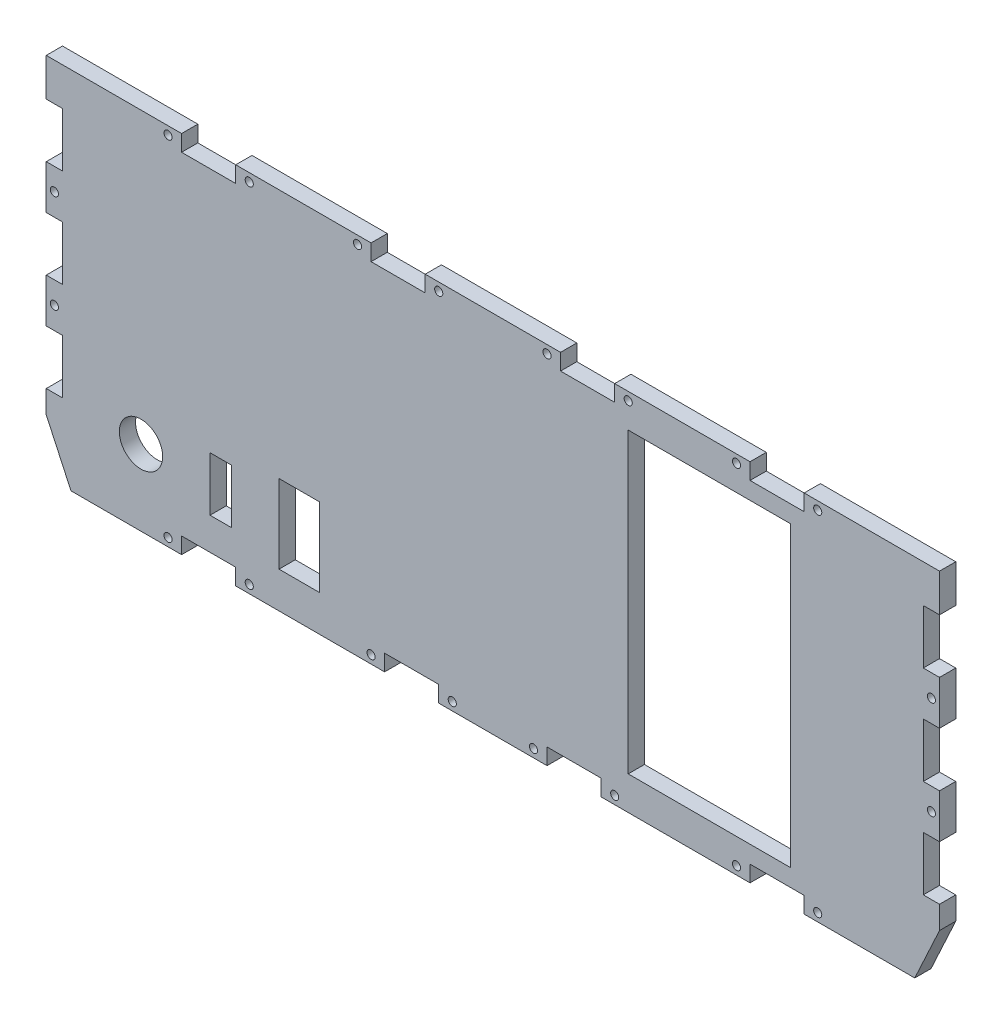
SolidWorks part; units mm, degrees
ref_plane "Plan de face" through (0, 0, 0) normal (0, 0, 1) x (1, 0, 0)
ref_plane "Plan de dessus" through (0, 0, 0) normal (0, 1, 0) x (1, 0, 0)
ref_plane "Plan de droite" through (0, 0, 0) normal (1, 0, 0) x (0, 0, -1)
sketch "Esquisse1" plane through (0, 0, 0) normal (0, 0, 1) x (1, 0, 0)
  line L0 (0, 124.9429) -> (0, -204.46) construction
  line L1 (-165, 96.73) -> (165, 96.73)
  line L2 (165, 96.73) -> (165, -18.27)
  line L3 (165, -18.27) -> (123, -109.0224)
  line L4 (123, -109.0224) -> (-123, -109.0224)
  line L5 (-211.9802, 0) -> (248.5953, 0) construction
  line L6 (-123, -109.0224) -> (-165, -18.27)
  line L7 (-165, -18.27) -> (-165, 96.73)
  dimension "D2" = 165
  dimension "D3" = 330
  dimension "D4" = 100
  dimension "D5" = 115
  dimension "D6" = 100
  dimension "D7" = 246
  dimension "D8" = 205.7524
  dimension "D9" = 96.73
  dimension "D10" = 115
extrude "Boss.-Extru.1" add sketch "Esquisse1" along normal blind 6
sketch "Esquisse3" plane through (0, 0, 0) normal (0, 0, -1) x (-1, 0, 0)
  line L0 (165, 96.73) -> (165, -18.27) construction
  line L1 (159, 46.44) -> (159, 26.44)
  line L2 (165, 46.44) -> (159, 46.44)
  line L3 (159, 82.73) -> (159, 62.73)
  line L4 (165, 62.73) -> (159, 62.73)
  line L5 (123, -109.0224) -> (-123, -109.0224) construction
  line L6 (165, 82.73) -> (165, 62.73)
  line L7 (165, 82.73) -> (159, 82.73)
  line L8 (159, 10.15) -> (159, -9.85)
  line L9 (165, -9.85) -> (159, -9.85)
  line L10 (-20, -38.02) -> (-20, -32.02)
  line L11 (115, -38.02) -> (95, -38.02)
  line L12 (115, -38.02) -> (115, -32.02)
  line L13 (115, -32.02) -> (95, -32.02)
  line L15 (0, -209.4812) -> (0, 177.1799) construction
  line L16 (-110, 84.355) -> (-50, 84.355)
  line L17 (-165, 82.73) -> (-159, 82.73)
  line L18 (95, -38.02) -> (95, -32.02)
  line L19 (40, -38.02) -> (20, -38.02)
  line L20 (40, -38.02) -> (40, -32.02)
  line L21 (40, -32.02) -> (20, -32.02)
  line L22 (-165, 82.73) -> (-165, 62.73)
  line L23 (-165, 62.73) -> (-159, 62.73)
  line L24 (-159, 82.73) -> (-159, 62.73)
  line L25 (-165, 46.44) -> (-159, 46.44)
  line L26 (-165, 46.44) -> (-165, 26.44)
  line L27 (-165, 26.44) -> (-159, 26.44)
  line L28 (-159, 46.44) -> (-159, 26.44)
  line L29 (-165, 10.15) -> (-159, 10.15)
  line L30 (-165, 96.73) -> (165, 96.73) construction
  line L31 (115, 96.73) -> (95, 96.73)
  line L32 (115, 96.73) -> (115, 90.73)
  line L33 (115, 90.73) -> (95, 90.73)
  line L34 (95, 96.73) -> (95, 90.73)
  line L35 (-25, 96.73) -> (-25, 90.73)
  line L36 (45, 96.73) -> (25, 96.73)
  line L37 (45, 96.73) -> (45, 90.73)
  line L38 (45, 90.73) -> (25, 90.73)
  line L39 (25, 96.73) -> (25, 90.73)
  line L40 (-45, 90.73) -> (-25, 90.73)
  line L41 (-45, 96.73) -> (-45, 90.73)
  line L42 (-45, 96.73) -> (-25, 96.73)
  line L43 (-95, 96.73) -> (-95, 90.73)
  line L44 (-115, 90.73) -> (-95, 90.73)
  line L45 (-115, 96.73) -> (-115, 90.73)
  line L46 (-115, 96.73) -> (-95, 96.73)
  line L47 (-165, 10.15) -> (-165, -9.85)
  line L48 (20, -38.02) -> (20, -32.02)
  line L49 (-40, -32.02) -> (-20, -32.02)
  line L50 (-40, -38.02) -> (-40, -32.02)
  line L51 (-40, -38.02) -> (-20, -38.02)
  line L52 (-165, -9.85) -> (-159, -9.85)
  line L53 (165, 10.15) -> (165, -9.85)
  line L54 (104.5, -20.145) -> (96.5, -20.145)
  line L55 (104.5, -20.145) -> (104.5, -0.145)
  line L56 (-159, 10.15) -> (-159, -9.85)
  line L57 (-95, -38.02) -> (-95, -32.02)
  line L58 (-115, -32.02) -> (-95, -32.02)
  line L59 (-115, -38.02) -> (-115, -32.02)
  line L60 (-115, -38.02) -> (-95, -38.02)
  line L61 (104.5, -0.145) -> (96.5, -0.145)
  line L62 (-110, 84.355) -> (-110, -25.645)
  line L63 (-110, -25.645) -> (-50, -25.645)
  line L64 (-50, 84.355) -> (-50, -25.645)
  line L65 (-165, -18.27) -> (-165, 96.73) construction
  line L66 (165, 10.15) -> (159, 10.15)
  line L67 (96.5, -20.145) -> (96.5, -0.145)
  line L68 (79, -24.645) -> (64, -24.645)
  line L69 (79, -24.645) -> (79, 4.355)
  line L70 (79, 4.355) -> (64, 4.355)
  line L71 (64, -24.645) -> (64, 4.355)
  line L72 (165, 26.44) -> (159, 26.44)
  line L73 (165, 46.44) -> (165, 26.44)
  circle A0 centre (130, -10.145) radius 8
  dimension "D44" = 16
  dimension "D45" = 21.875
  dimension "D42" = 35
  dimension "D47" = 17.5
  dimension "D5" = 6
  dimension "D6" = 20
  dimension "D7" = 60
  dimension "D8" = 55
  dimension "D10" = 20
  dimension "D11" = 20
  dimension "D12" = 50
  dimension "D13" = 50
  dimension "D14" = 6
  dimension "D15" = 110
  dimension "D16" = 50
  dimension "D17" = 55
  dimension "D18" = 20
  dimension "D19" = 20
  dimension "D20" = 20
  dimension "D21" = 6
  dimension "D22" = 6
  dimension "D23" = 20
  dimension "D24" = 71.0024
  dimension "D25" = 71.0024
  dimension "D27" = 101
  dimension "D29" = 6.375
  dimension "D31" = 6
  dimension "D32" = 6
  dimension "D33" = 6
  dimension "D34" = 14
  dimension "D35" = 16.29
  dimension "D36" = 16.29
  dimension "D37" = 20
  dimension "D38" = 8
  dimension "D39" = 15
  dimension "D40" = 29
  dimension "D41" = 7.375
  dimension "D46" = 11.875
extrude "Enlèv. mat.-Extru.2" cut sketch "Esquisse3" against normal blind 6
sketch "Esquisse4" plane through (0, 0, 0) normal (0, 0, -1) x (-1, 0, 0)
  line L1 (115, 90.73) -> (115, 96.73) construction
  line L2 (120.102, -35.02) -> (4.7601, -35.02) construction
  line L3 (20, -32.02) -> (20, -38.02) construction
  line L4 (40, -38.02) -> (40, -32.02) construction
  line L5 (95, -32.02) -> (95, -38.02) construction
  line L6 (26.5287, 81.73) -> (-31.7243, 81.73) construction
  line L7 (115, -38.02) -> (115, -32.02) construction
  line L9 (-120.102, -35.02) -> (-4.7601, -35.02) construction
  line L10 (-25, 96.73) -> (25, 96.73) construction
  line L11 (143.8632, 93.73) -> (-5, 93.73) construction
  line L12 (45, 96.73) -> (95, 96.73) construction
  line L13 (-162, -27.3544) -> (-162, 100.425) construction
  line L14 (95, 96.73) -> (95, 90.73) construction
  line L15 (45, 90.73) -> (45, 96.73) construction
  line L16 (25, 96.73) -> (25, 90.73) construction
  line L17 (0, 142.2997) -> (0, -202.2086) construction
  line L18 (-165, -18.27) -> (-165, -9.85) construction
  line L19 (-80, 84.355) -> (-80, -25.645) construction
  line L22 (162, -8.8216) -> (162, 103.5789) construction
  line L25 (-50, 84.355) -> (-110, 84.355) construction
  line L26 (-110, -25.645) -> (-50, -25.645) construction
  line L27 (-159, 46.44) -> (-165, 46.44) construction
  line L28 (-165, 26.44) -> (-159, 26.44) construction
  circle A0 centre (162, 18.29) radius 1.5
  circle A1 centre (120, -35.02) radius 1.5
  circle A2 centre (162, 54.585) radius 1.5
  circle A3 centre (90, -35.02) radius 1.5
  circle A4 centre (45, -35.02) radius 1.5
  circle A6 centre (15, -35.02) radius 1.5
  circle A7 centre (-15, -35.02) radius 1.5
  circle A8 centre (-45, -35.02) radius 1.5
  circle A9 centre (-90, -35.02) radius 1.5
  circle A10 centre (120, 93.73) radius 1.5
  circle A11 centre (-120, -35.02) radius 1.5
  circle A12 centre (90, 93.73) radius 1.5
  circle A14 centre (50, 93.73) radius 1.5
  circle A15 centre (20, 93.73) radius 1.5
  circle A16 centre (-162, 18.29) radius 1.5
  circle A17 centre (-162, 54.585) radius 1.5
  circle A18 centre (-20, 93.73) radius 1.5
  circle A19 centre (-50, 93.73) radius 1.5
  circle A20 centre (-90, 93.73) radius 1.5
  circle A21 centre (-120, 93.73) radius 1.5
  dimension "D10" = 3
  dimension "D11" = 3
  dimension "D12" = 3
  dimension "D13" = 5
  dimension "D14" = 5
  dimension "D29" = 3
  dimension "D30" = 8.15
  dimension "D31" = 3
  dimension "D33" = 3
  dimension "D34" = 3
  dimension "D40" = 5
  dimension "D8" = 5
  dimension "D15" = 5
  dimension "D16" = 5
  dimension "D17" = 3
  dimension "D21" = 3
  dimension "D22" = 3
  dimension "D27" = 8.145
  dimension "D9" = 3
  dimension "D28" = 3
  dimension "D36" = 15
  dimension "D38" = 5
  dimension "D42" = 5
extrude "Enlèv. mat.-Extru.3" cut sketch "Esquisse4" against normal blind 6
sketch "Esquisse5" plane through (0, 0, 0) normal (0, 0, -1) x (-1, 0, 0)
  line L0 (45, 96.73) -> (95, 96.73) construction
  line L1 (209.7155, -38.02) -> (-246.3297, -38.02)
  line L2 (209.7155, -38.02) -> (209.7155, -174.249)
  line L3 (209.7155, -174.249) -> (-246.3297, -174.249)
  line L4 (-246.3297, -38.02) -> (-246.3297, -174.249)
  dimension "D1" = 134.75
extrude "Enlèv. mat.-Extru.4" cut sketch "Esquisse5" against normal blind 6
